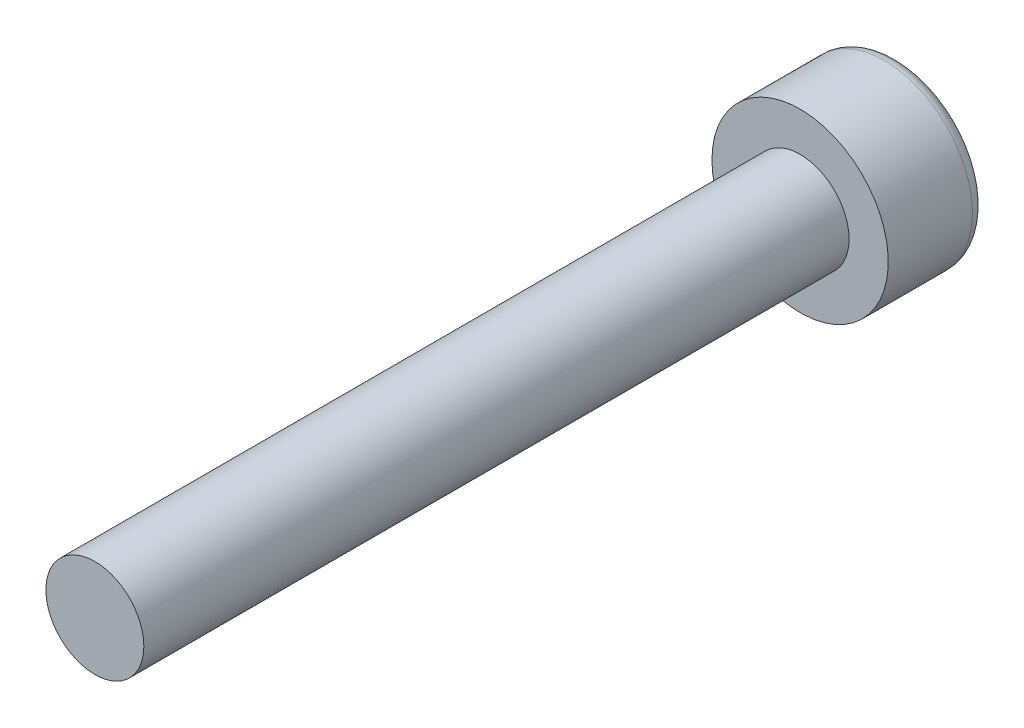
SolidWorks part; units mm, degrees
material "Acero aleado"
ref_plane "Alzado" through (0, 0, 0) normal (0, 0, 1) x (1, 0, 0)
ref_plane "Planta" through (0, 0, 0) normal (0, 1, 0) x (1, 0, 0)
ref_plane "Vista lateral" through (0, 0, 0) normal (1, 0, 0) x (0, 0, -1)
sketch "Croquis1" plane through (0, 0, 0) normal (0, 0, 1) x (1, 0, 0)
  circle A0 centre (0, 0) radius 1.25
  dimension "D1" = 2.5
extrude "Saliente-Extruir1" add sketch "Croquis1" along normal blind 18
sketch "Croquis2" plane through (0, 0, 0) normal (0, 0, -1) x (-1, 0, 0)
  circle A0 centre (0, 0) radius 2.25
  dimension "D1" = 4.5
extrude "Saliente-Extruir2" add sketch "Croquis2" along normal blind 2.5
sketch "Croquis3" plane through (0, 0, -2.5) normal (0, 0, -1) x (-1, 0, 0)
  line L1 (0, -1.1547) -> (1, -0.5774)
  line L2 (1, -0.5774) -> (1, 0.5774)
  line L3 (1, 0.5774) -> (0, 1.1547)
  line L4 (0, 1.1547) -> (-1, 0.5774)
  line L5 (-1, 0.5774) -> (-1, -0.5774)
  line L6 (-1, -0.5774) -> (0, -1.1547)
  circle A0 centre (0, 0) radius 1 construction
  dimension "D1" = 2
extrude "Cortar-Extruir1" cut sketch "Croquis3" against normal blind 1.5
fillet "Redondeo1" radius 0.35 1 edges at (-2.25, 0, -2.5)
